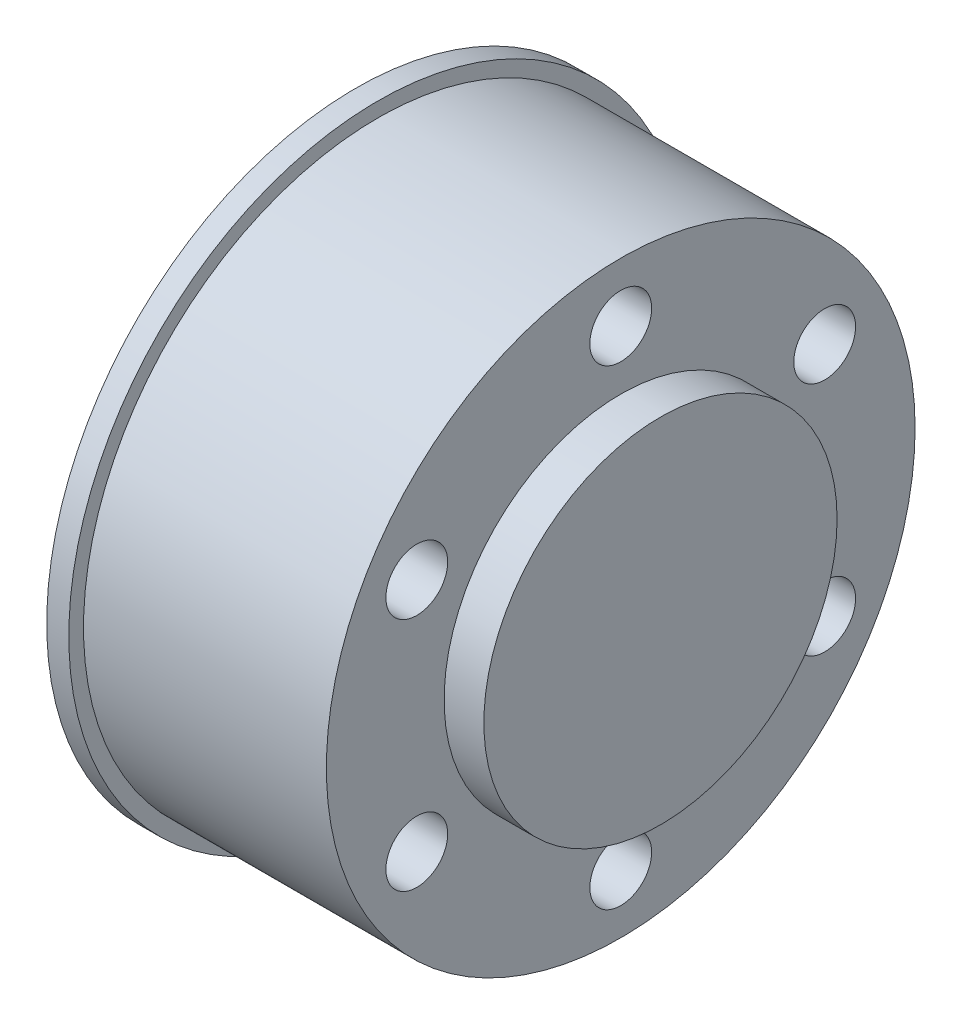
SolidWorks part; units mm, degrees
ref_plane "Front Plane" through (0, 0, 0) normal (0, 0, 1) x (1, 0, 0)
ref_plane "Top Plane" through (0, 0, 0) normal (0, 1, 0) x (1, 0, 0)
ref_plane "Right Plane" through (0, 0, 0) normal (1, 0, 0) x (0, 0, -1)
sketch "Sketch2" plane through (0, 0, 0) normal (0, 1, 0) x (1, 0, 0)
  line L0 (0, 0) -> (0, 12)
  line L1 (0, 12) -> (-2.7, 12)
  line L2 (-2.7, 12) -> (-2.7, 20)
  line L3 (-2.7, 20) -> (-19.2, 20)
  line L4 (-19.2, 20) -> (-19.2, 21)
  line L5 (-19.2, 21) -> (-20.7, 21)
  line L6 (-20.7, 21) -> (-20.7, 17.6528)
  line L7 (0, 0) -> (-41.2311, 0) construction
  line L11 (-20.7, 14.5) -> (-20.7, 8)
  line L12 (-20.7, 8) -> (-15.7, 8)
  line L13 (-15.7, 8) -> (-15.7, 6)
  line L14 (-15.7, 6) -> (-14.7, 6)
  line L15 (-14.7, 6) -> (-14.7, 0)
  line L16 (-14.7, 0) -> (0, 0)
  line L17 (-20.7, 17.6528) -> (-20.7, 14.5)
  dimension "D1" = 12
  dimension "D2" = 2.7
  dimension "D3" = 8
  dimension "D4" = 16.5
  dimension "D5" = 1
  dimension "D6" = 1.5
  dimension "D8" = 8
  dimension "D9" = 6
  dimension "D10" = 5
  dimension "D13" = 1
revolve "Revolve1" add sketch "Sketch2" angle 360 about L7
sketch "Sketch3" plane through (-20.7, 0, 0) normal (-1, 0, 0) x (0, 0, 1)
  circle A0 centre (0, 16) radius 1.5
  circle A1 centre (13.8564, 7.9047) radius 1.5
  circle A2 centre (13.7739, -8.1429) radius 1.5
  circle A3 centre (-0.165, -16.0953) radius 1.5
  circle A4 centre (-14.0214, -8) radius 1.5
  circle A5 centre (-13.9389, 8.0476) radius 1.5
  dimension "D1" = 3
  dimension "D3" = 16
  dimension "D2" = 6
extrude "Cut-Extrude1" cut sketch "Sketch3" against normal blind 4
sketch "Sketch4" plane through (-2.7, 0, 0) normal (1, 0, 0) x (0, 0, -1)
  circle A0 centre (0, 16) radius 2.1
  circle A1 centre (13.8564, 8) radius 2.1
  circle A2 centre (13.8564, -8) radius 2.1
  circle A3 centre (0, -16) radius 2.1
  circle A4 centre (-13.8564, -8) radius 2.1
  circle A5 centre (-13.8564, 8) radius 2.1
  point P15 (0, 0)
  dimension "D1" = 4.2
  dimension "D2" = 16
  dimension "D3" = 6
extrude "Cut-Extrude2" cut sketch "Sketch4" against normal blind 10
